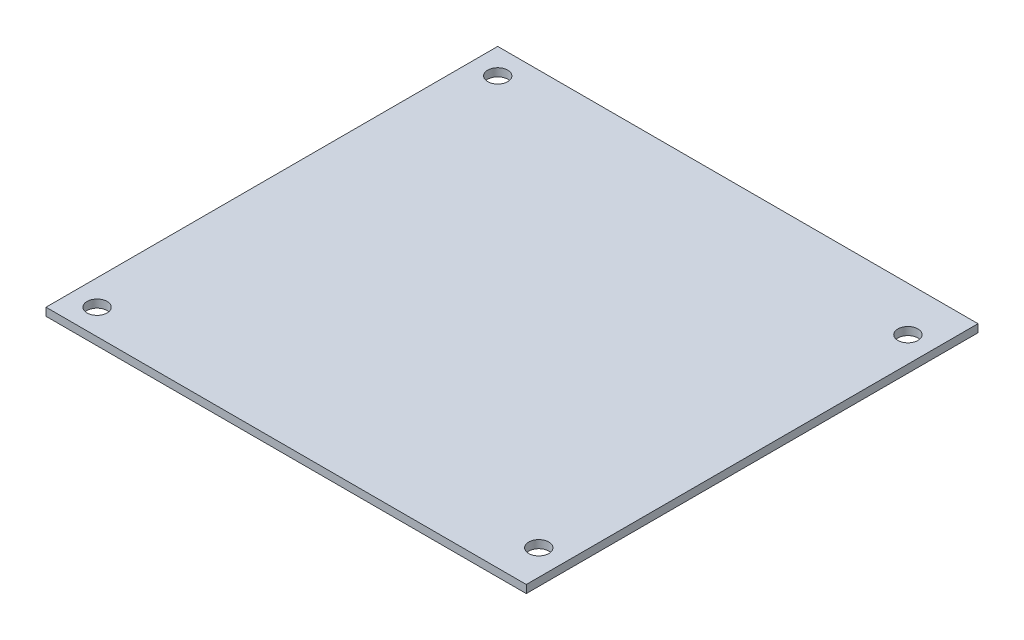
SolidWorks part; units mm, degrees
ref_plane "Front Plane" through (0, 0, 0) normal (0, 0, 1) x (1, 0, 0)
ref_plane "Top Plane" through (0, 0, 0) normal (0, 1, 0) x (1, 0, 0)
ref_plane "Right Plane" through (0, 0, 0) normal (1, 0, 0) x (0, 0, -1)
sketch "Sketch1" plane through (0, 0, 0) normal (0, 1, 0) x (1, 0, 0)
  line L1 (-47.95, -45.1) -> (47.95, -45.1)
  line L2 (-47.95, -45.1) -> (-47.95, 45.1)
  line L3 (-47.95, 45.1) -> (47.95, 45.1)
  line L4 (47.95, -45.1) -> (47.95, 45.1)
  line L5 (-47.95, -45.1) -> (47.95, 45.1) construction
  line L6 (-47.95, 45.1) -> (47.95, -45.1) construction
  circle A0 centre (-42.85, 40) radius 2
  circle A1 centre (42.85, 36.2) radius 2
  circle A2 centre (-42.85, -40) radius 2
  circle A3 centre (42.85, -37.5) radius 2
  point P0 (0, 0)
  point P6 (42.85, -37.5)
  point P7 (42.85, 36.2)
  point P8 (-42.85, 40)
  point P9 (-42.85, -40)
extrude "Boss-Extrude1" add sketch "Sketch1" along normal blind 1.58
